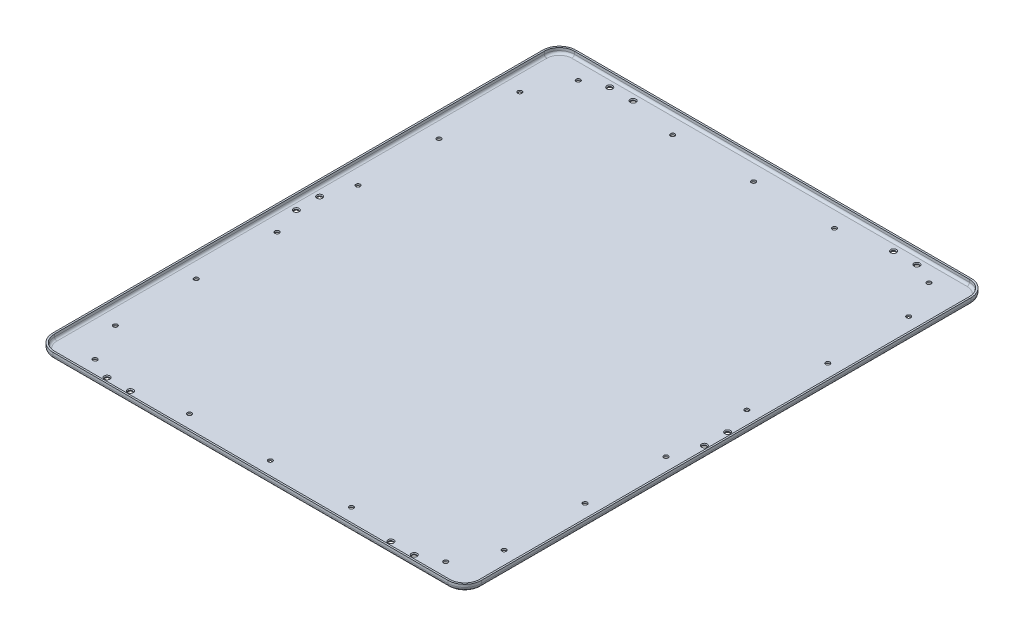
SolidWorks part; units mm, degrees
ref_plane "front" through (0, 0, 0) normal (0, 0, 1) x (1, 0, 0)
ref_plane "top" through (0, 0, 0) normal (0, 1, 0) x (1, 0, 0)
ref_plane "right" through (0, 0, 0) normal (1, 0, 0) x (0, 0, -1)
sketch "Sketch1" plane through (0, 0, 0) normal (0, 1, 0) x (1, 0, 0)
  line L1 (-201.803, 489.2802) -> (201.803, 489.2802)
  line L2 (-201.803, 489.2802) -> (-201.803, -3.4798)
  line L3 (-201.803, -3.4798) -> (201.803, -3.4798)
  line L4 (201.803, 489.2802) -> (201.803, -3.4798)
  point P4 (0, -3.4798)
  dimension "D1" = 3.4798
  dimension "D2" = 403.606
  dimension "D3" = 492.76
extrude "Extrude1" add sketch "Sketch1" along normal blind 6.35
fillet "Fillet1" radius 15.748 4 edges at (-201.803, 3.175, 3.4798) (-201.803, 3.175, -489.2802) (201.803, 3.175, -489.2802) (201.803, 3.175, 3.4798)
fillet "Fillet2" radius 3.81 8 edges at (197.1905, 0, -1.1327) (201.803, 0, -242.9002) (197.1905, 0, -484.6677) (0, 0, -489.2802) (-197.1905, 0, -484.6677) (-201.803, 0, -242.9002) (-197.1905, 0, -1.1327) (0, 0, 3.4798)
shell "Shell1" thickness 1.6002
sketch "Sketch4" plane through (0, 0, 0) normal (0, 1, 0) x (1, 0, 0)
  line L0 (0, 0) -> (0, 70.8172) construction
  line L1 (-201.803, 242.9002) -> (-87.9176, 242.9002) construction
  line L2 (-201.803, 489.2802) -> (-201.803, -3.4798) construction
  line L3 (201.803, 489.2802) -> (201.803, -3.4798) construction
  line L4 (-201.803, -3.4798) -> (201.803, -3.4798) construction
  circle A0 centre (183.134, 204.8002) radius 2.0447
  circle A1 centre (0, 15.367) radius 2.0447
  circle A2 centre (183.134, 128.6002) radius 2.0447
  circle A3 centre (183.134, 433.4002) radius 2.0447
  circle A6 centre (183.134, 281.0002) radius 2.0447
  circle A7 centre (183.134, 357.2002) radius 2.0447
  circle A9 centre (-183.134, 357.2002) radius 2.0447
  circle A10 centre (-183.134, 281.0002) radius 2.0447
  circle A11 centre (183.134, 52.4002) radius 2.0447
  circle A12 centre (-183.134, 128.6002) radius 2.0447
  circle A13 centre (-183.134, 204.8002) radius 2.0447
  circle A14 centre (165.1, 15.367) radius 2.0447
  circle A15 centre (-183.134, 52.4002) radius 2.0447
  circle A16 centre (-183.134, 433.4002) radius 2.0447
  circle A17 centre (-165.1, 470.4334) radius 2.0447
  circle A18 centre (-76.2, 470.4334) radius 2.0447
  circle A19 centre (76.2, 15.367) radius 2.0447
  circle A20 centre (76.2, 470.4334) radius 2.0447
  circle A21 centre (165.1, 470.4334) radius 2.0447
  circle A22 centre (-76.2, 15.367) radius 2.0447
  circle A23 centre (-165.1, 15.367) radius 2.0447
  circle A24 centre (0, 470.4334) radius 2.0447
  dimension "D3" = 4.0894
  dimension "D1" = 18.669
  dimension "D2" = 18.8468
  dimension "D4" = 76.2
  dimension "D5" = 76.2
  dimension "D6" = 76.2
  dimension "D7" = 76.2
  dimension "D8" = 88.9
  dimension "D9" = 88.9
  dimension "D10" = 38.1
  dimension "D13" = 76.2
extrude "Cut-Extrude2" cut sketch "Sketch4" along normal through all
sketch "Sketch5" plane through (0, 0, 0) normal (0, 1, 0) x (1, 0, 0)
  line L0 (0, 0) -> (0, 68.0698) construction
  line L2 (-201.803, 489.2802) -> (-201.803, -3.4798) construction
  line L3 (-201.803, -3.4798) -> (201.803, -3.4798) construction
  line L4 (133.6548, -3.4798) -> (133.6548, 12.9474) construction
  line L5 (-201.803, 242.9002) -> (-161.7623, 242.9002) construction
  line L7 (201.803, 12.2682) -> (201.803, 473.5322) construction
  line L8 (-201.803, 473.5322) -> (-201.803, 12.2682) construction
  circle A0 centre (122.6566, 6.1722) radius 2.0447
  circle A1 centre (144.653, 6.1722) radius 2.0447
  circle A2 centre (-122.6566, 6.1722) radius 2.0447
  circle A3 centre (-144.653, 6.1722) radius 2.0447
  circle A4 centre (-144.653, 479.6282) radius 2.0447
  circle A5 centre (-122.6566, 479.6282) radius 2.0447
  circle A6 centre (122.6566, 479.6282) radius 2.0447
  circle A7 centre (144.653, 479.6282) radius 2.0447
  circle A8 centre (-192.151, 231.902) radius 2.0447
  circle A9 centre (-192.151, 253.8984) radius 2.0447
  circle A14 centre (192.151, 253.8984) radius 2.0447
  circle A15 centre (192.151, 231.902) radius 2.0447
  dimension "D4" = 4.0894
  dimension "D1" = 9.652
  dimension "D2" = 21.9964
  dimension "D3" = 133.6548
  dimension "D5" = 21.9964
  dimension "D6" = 9.652
  dimension "D9" = 57.15
extrude "Cut-Extrude4" cut sketch "Sketch5" along normal through all
chamfer "Chamfer1" distance 0.8128 angle 39 12 edges at (-144.653, 1.6002, -4.1275) (-122.6566, 1.6002, -4.1275) (122.6566, 1.6002, -4.1275) (144.653, 1.6002, -4.1275) (192.151, 1.6002, -229.8573) (192.151, 1.6002, -251.8537) (-144.653, 1.6002, -477.5835) (-122.6566, 1.6002, -477.5835) (122.6566, 1.6002, -477.5835) (144.653, 1.6002, -477.5835) (-192.151, 1.6002, -251.8537) (-192.151, 1.6002, -229.8573)
